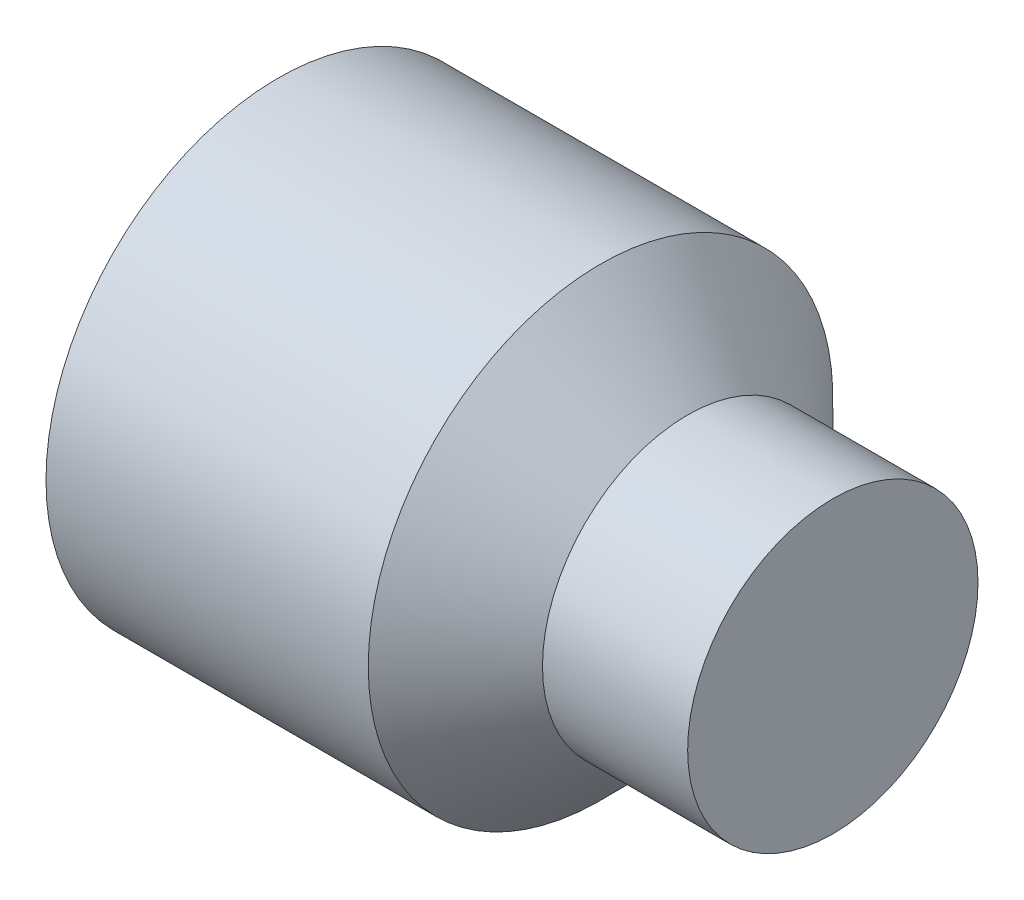
SolidWorks part; units mm, degrees
revolve "BaseBody" add sketch "BodySke" angle 360 about L5
sketch "BodySke" plane through (0, 0, 0) normal (0, 0, 1) x (1, 0, 0)
  line L0 (0, 0) -> (0, 1.61)
  line L1 (0, 1.61) -> (0.2252, 2)
  line L2 (0.2252, 2) -> (3, 2)
  line L3 (3, 2) -> (3.75, 1.25)
  line L4 (5, 0) -> (0, 0)
  line L5 (-12.7, 0) -> (88.9, 0) construction
  line L6 (3.75, 1.25) -> (5, 1.25)
  line L7 (5, 1.25) -> (5, 0)
  line L8 (0, -1.61) -> (0.2252, -2) construction
  line L9 (3.75, -1.25) -> (5, -1.25) construction
  line L10 (0.35, 15.875) -> (0.35, -3.175) construction
  dimension "Diameter" = 4
  dimension "Drive_ch_ang" = 60
  dimension "Minor_dia" = 3.22
  dimension "Dog_dia" = 2.5
  dimension "Dog_len" = 1.25
  dimension "Length" = 5
  dimension "D1" = 45
  dimension "Advance" = 0.7
cosmetic thread "ThreadCosmetic" [suppressed] parameters "Thread_minor"=3.22
ref_plane "Plane1" through (0, 0, 0) normal (0, 0, 1) x (1, 0, 0)
ref_plane "Plane2" through (0, 0, 0) normal (0, 1, 0) x (1, 0, 0)
ref_plane "Plane3" through (0, 0, 0) normal (1, 0, 0) x (0, 0, -1)
sketch "Sketch2" plane through (0, 0, 0) normal (-1, 0, 0) x (0, 0, 1)
  line L0 (0.5774, 1) -> (-0.5774, 1)
  line L1 (-0.5774, 1) -> (-1.1547, 0)
  line L2 (0.5774, 1) -> (1.1547, 0)
  line L3 (0.5774, -1) -> (1.1547, 0)
  line L4 (0.5774, -1) -> (-0.5774, -1)
  line L5 (-0.5774, -1) -> (-1.1547, 0)
  dimension "Hex_size" = 2
  dimension "D2" = 1
  dimension "D3" = 1
extrude "Hex" cut sketch "Sketch2" against normal blind 1.5
sketch "ThdSchSke" plane through (0, 0, 0) normal (0, 0, 1) x (1, 0, 0)
  line L0 (0.2252, -1.61) -> (-0.0479, -2)
  line L1 (0.2252, -1.61) -> (0.4982, -2)
  line L2 (0.4982, -2) -> (0.4982, -2.5)
  line L3 (-3.175, 0) -> (5.1513, 0) construction
  line L4 (0.2252, 2) -> (0.2252, -2) construction
  line L5 (0.4982, -2.5) -> (-0.0479, -2.5)
  line L6 (-0.0479, -2.5) -> (-0.0479, -2)
  dimension "Thread_minor" = 3.22
  dimension "Diameter" = 4
revolve "ThreadSchematic" [suppressed] cut sketch "ThdSchSke" angle 360 about L3
pattern_linear "ThdSchPat" [suppressed]
equation "\"D2@Sketch2\" = \"Hex_size@Sketch2\" / 2"
equation "\"D3@Sketch2\" = \"Hex_size@Sketch2\" / 2"
equation "\"Thread_minor@ThreadCosmetic\" = \"Minor_dia@BodySke\""
equation "\"Thread_minor@ThdSchSke\" = \"Thread_minor@ThreadCosmetic\""
equation "\"Diameter@ThdSchSke\" = \"Diameter@BodySke\""
equation "\"Overcut@ThdSchSke\" = \"Diameter@BodySke\" * 1.25"
equation "\"Num_threads@ThdSchPat\" = int( (\"Length@BodySke\" - ( ( ( \"Diameter@BodySke\" - \"Minor_dia@BodySke\" ) * 0.5 ) / tan( \"Drive_ch_ang@BodySke\" * 0.017453292 ) ) - \"Dog_len@BodySke\" ) / \"Advance@BodySke\" + 0.999 )  + 1"
equation "\"Advance@ThdSchPat\" = (\"Length@BodySke\" - ( ( ( \"Diameter@BodySke\" - \"Minor_dia@BodySke\" ) * 0.5 ) / tan( \"Drive_ch_ang@BodySke\" * 0.017453292 ) ) - \"Dog_len@BodySke\" ) /  (\"Num_threads@ThdSchPat\" - 1) 'relax it"
equation "\"Num_threads@ThdSchPat\" = \"Num_threads@ThdSchPat\" - sgn( \"Num_threads@ThdSchPat\" - 1) '---chamfered tips only---"
